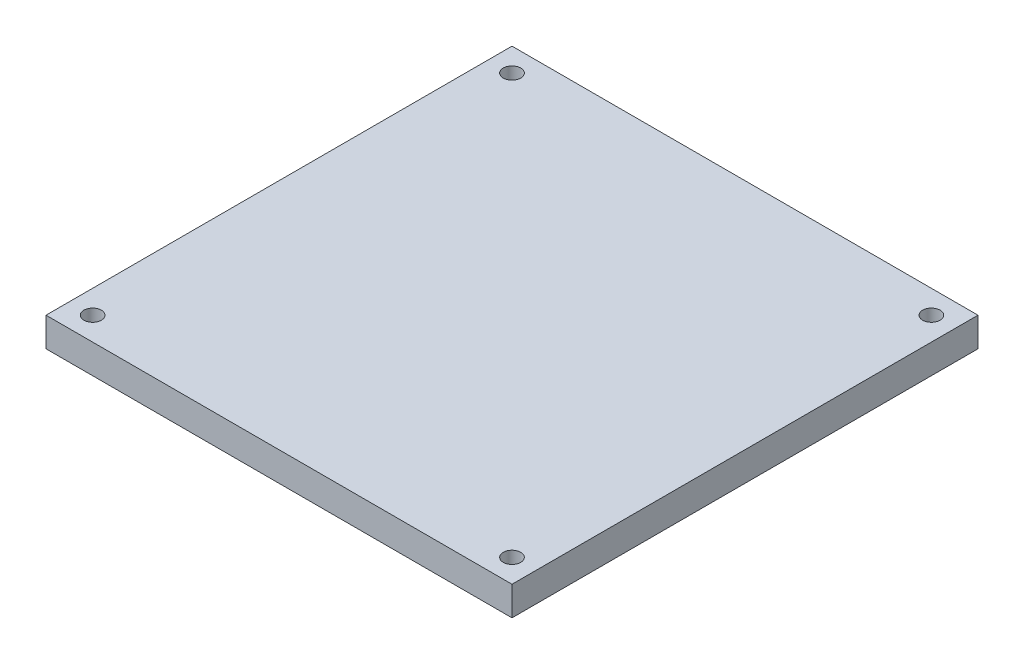
SolidWorks part; units mm, degrees
material "ABS"
ref_plane "Plan de face" through (0, 0, 0) normal (0, 0, 1) x (1, 0, 0)
ref_plane "Plan de dessus" through (0, 0, 0) normal (0, 1, 0) x (1, 0, 0)
ref_plane "Plan de droite" through (0, 0, 0) normal (1, 0, 0) x (0, 0, -1)
sketch "Esquisse1" plane through (0, 0, 0) normal (0, 1, 0) x (1, 0, 0)
  line L0 (0, 0) -> (0, 40) construction
  line L1 (-40, 40) -> (40, 40)
  line L2 (-40, 40) -> (-40, -40)
  line L3 (-40, -40) -> (40, -40)
  line L4 (40, 40) -> (40, -40)
  line L5 (0, 0) -> (40, 0) construction
  circle A0 centre (-36, 36) radius 1.5
  circle A1 centre (36, 36) radius 1.5
  circle A2 centre (-36, -36) radius 1.5
  circle A3 centre (36, -36) radius 1.5
  dimension "D4" = 3
  dimension "D1" = 80
  dimension "D2" = 4
  dimension "D3" = 4
extrude "Extrusion1" add sketch "Esquisse1" along normal blind 5
